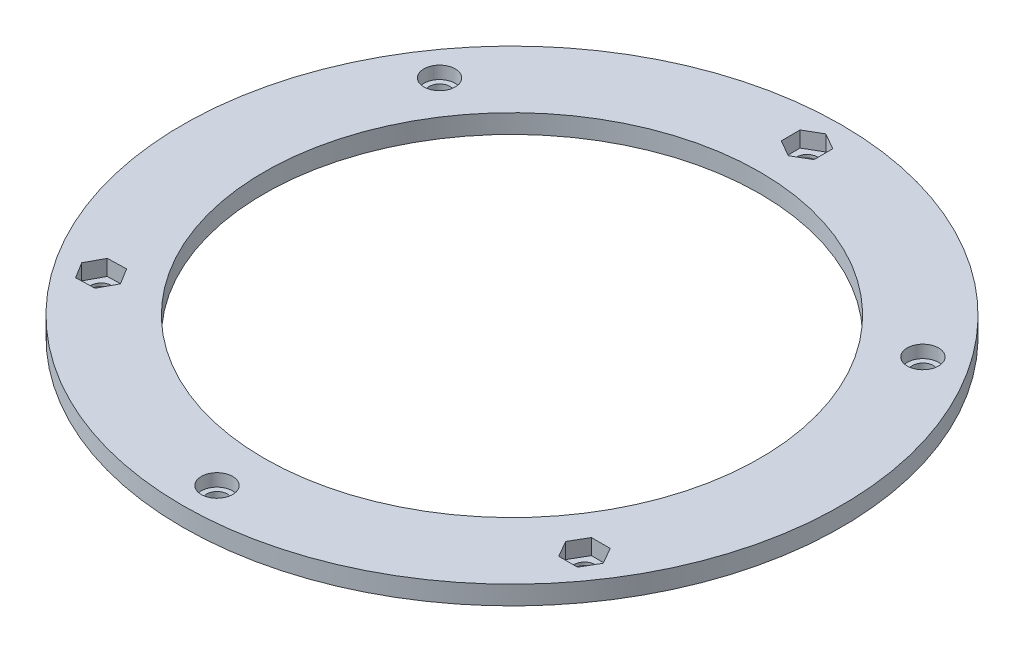
SolidWorks part; units mm, degrees
ref_plane "Front Plane" through (0, 0, 0) normal (0, 0, 1) x (1, 0, 0)
ref_plane "Top Plane" through (0, 0, 0) normal (0, 1, 0) x (1, 0, 0)
ref_plane "Right Plane" through (0, 0, 0) normal (1, 0, 0) x (0, 0, -1)
sketch "Sketch1" plane through (0, 0, 0) normal (0, 1, 0) x (1, 0, 0)
  circle A0 centre (0, 0) radius 39.5
  circle A1 centre (0, 0) radius 52.5
  dimension "D1" = 79
  dimension "D2" = 105
extrude "Boss-Extrude1" add sketch "Sketch1" along normal blind 3
sketch "Sketch2" plane through (0, 3, 0) normal (0, 1, 0) x (1, 0, 0)
  line L0 (0, 0) -> (-52.5, 0) construction
  line L1 (0, 0) -> (-43.0055, 30.1128) construction
  line L2 (0, 0) -> (43.0055, 30.1128) construction
  line L3 (0, 0) -> (43.0055, -30.1128) construction
  line L4 (0, 0) -> (-43.0055, -30.1128) construction
  line L5 (0, 0) -> (0, 39.5) construction
  line L6 (0, 0) -> (52.5, 0) construction
  circle A1 centre (0, 47) radius 1.65
  circle A4 centre (0, -47) radius 1.65
  circle A5 centre (0, 0) radius 52.5 construction
  circle A7 centre (-38.5001, 26.9581) radius 1.65
  circle A8 centre (38.5001, 26.9581) radius 1.65
  circle A9 centre (38.5001, -26.9581) radius 1.65
  circle A10 centre (-38.5001, -26.9581) radius 1.65
  circle A11 centre (0, 0) radius 39.5 construction
  dimension "D1" = 47
  dimension "D2" = 3.3
  dimension "D3" = 47
  dimension "D4" = 47
  dimension "D5" = 47
  dimension "D6" = 47
  dimension "D7" = 47
  dimension "D8" = 35
  dimension "D9" = 35
  dimension "D10" = 35
  dimension "D11" = 35
extrude "Cut-Extrude1" cut sketch "Sketch2" against normal through all
sketch "Sketch3" plane through (0, 3, 0) normal (0, 1, 0) x (1, 0, 0)
  circle A0 centre (-38.5001, 26.9581) radius 2.5
  circle A1 centre (38.5001, 26.9581) radius 2.5
  circle A2 centre (0, -47) radius 2.5
  dimension "D1" = 5
extrude "Cut-Extrude2" cut sketch "Sketch3" against normal blind 2
sketch "Sketch4" plane through (0, 3, 0) normal (0, 1, 0) x (1, 0, 0)
  line L1 (-0.0123, 50) -> (-2.6042, 48.4894)
  line L2 (-2.6042, 48.4894) -> (-2.5919, 45.4894)
  line L3 (-2.5919, 45.4894) -> (0.0123, 44)
  line L4 (0.0123, 44) -> (2.6042, 45.5106)
  line L5 (2.6042, 45.5106) -> (2.5919, 48.5106)
  line L6 (2.5919, 48.5106) -> (-0.0123, 50)
  line L7 (-40.0754, -24.4049) -> (-41.4989, -27.0457)
  line L8 (-41.4989, -27.0457) -> (-39.9236, -29.5989)
  line L9 (-39.9236, -29.5989) -> (-36.9249, -29.5113)
  line L10 (-36.9249, -29.5113) -> (-35.5014, -26.8705)
  line L11 (-35.5014, -26.8705) -> (-37.0766, -24.3173)
  line L12 (-37.0766, -24.3173) -> (-40.0754, -24.4049)
  line L13 (35.5001, -26.9581) -> (37.0001, -29.5562)
  line L14 (37.0001, -29.5562) -> (40.0001, -29.5562)
  line L15 (40.0001, -29.5562) -> (41.5001, -26.9581)
  line L16 (41.5001, -26.9581) -> (40.0001, -24.36)
  line L17 (40.0001, -24.36) -> (37.0001, -24.36)
  line L18 (37.0001, -24.36) -> (35.5001, -26.9581)
  circle A0 centre (0, 47) radius 3 construction
  circle A1 centre (-38.5001, -26.9581) radius 3 construction
  circle A2 centre (38.5001, -26.9581) radius 3 construction
  dimension "D1" = 6
extrude "Cut-Extrude3" cut sketch "Sketch4" against normal blind 2.5 contours L1 L2 L3 L4 L5 L6 | L7 L8 L9 L10 L11 L12 | L13 L14 L15 L16 L17 L18
